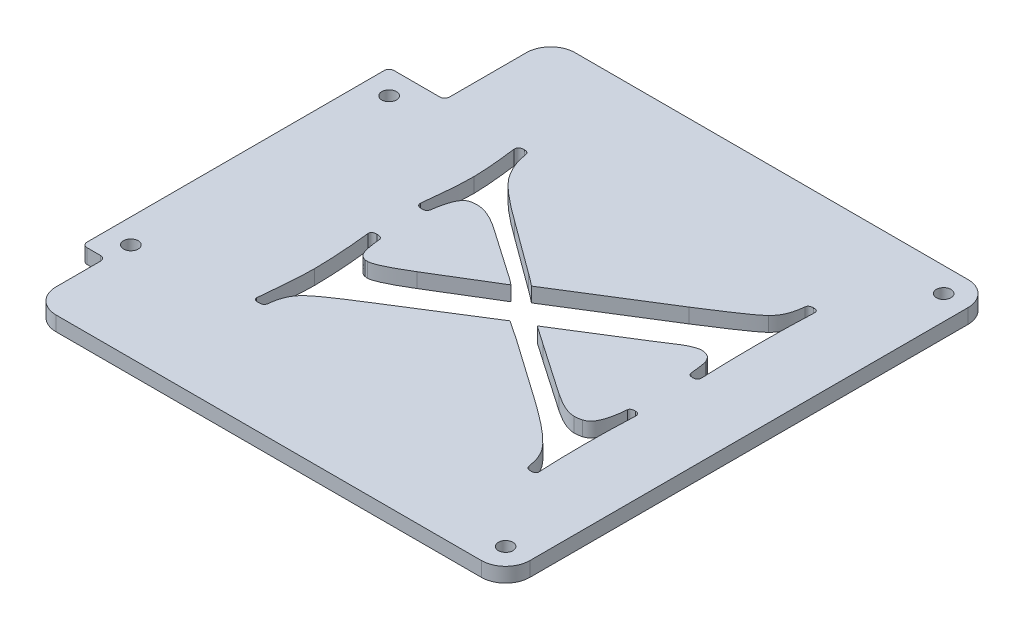
SolidWorks part; units mm, degrees
ref_plane "Front Plane" through (0, 0, 0) normal (0, 0, 1) x (1, 0, 0)
ref_plane "Top Plane" through (0, 0, 0) normal (0, 1, 0) x (1, 0, 0)
ref_plane "Right Plane" through (0, 0, 0) normal (1, 0, 0) x (0, 0, -1)
ref_plane "Plane1" through (0, 23, 0) normal (0, 1, 0) x (1, 0, 0)
sketch "Sketch1" plane through (0, 23, 0) normal (0, 1, 0) x (1, 0, 0)
  line L0 (98.3054, 50) -> (98.3054, 28.2195)
  line L1 (189.0458, 50) -> (98.3054, 50)
  line L2 (189.0458, 50) -> (189.0458, -50)
  line L3 (189.0458, -50) -> (97.6502, -50)
  line L5 (98.3054, 28.2195) -> (86.88, 28.2195)
  line L6 (86.88, 28.2195) -> (86.88, -34.8422)
  line L7 (86.88, -34.8422) -> (91.6598, -34.8422)
  line L8 (91.6598, -34.8422) -> (91.6598, -50)
  line L9 (91.6598, -50) -> (97.6502, -50)
  line L10 (94.8054, 33.2195) -> (98.3054, 33.2195) construction
  line L11 (184.0458, 45) -> (184.0458, 50) construction
  line L12 (93.3054, 31.7195) -> (93.3054, 28.2195) construction
  line L13 (99.4745, -34.8422) -> (86.1225, -34.8422) construction
  line L14 (88.1598, -39.8422) -> (91.6598, -39.8422) construction
  line L15 (86.6598, -38.3422) -> (86.6598, -34.8422) construction
  line L16 (189.0458, 0) -> (190, 0) construction
  line L17 (190, -60) -> (190, 60) construction
  line L18 (105.0183, -40) -> (185.0183, -40) construction
  line L19 (105.0183, -40) -> (105.0183, 40) construction
  line L20 (105.0183, 40) -> (185.0183, 40) construction
  line L21 (185.0183, -40) -> (185.0183, 40) construction
  line L22 (184.0458, 45) -> (189.0458, 45) construction
  line L23 (184.0458, -45) -> (189.0458, -45) construction
  line L24 (184.0458, -45) -> (184.0458, -50) construction
  line L25 (91.88, 23.2195) -> (91.88, 28.2195) construction
  line L26 (91.88, 23.2195) -> (86.88, 23.2195) construction
  line L27 (91.88, -29.8422) -> (91.88, -34.8422) construction
  line L28 (91.88, -29.8422) -> (86.88, -29.8422) construction
  circle A0 centre (86.6598, -39.8422) radius 1.5 construction
  circle A1 centre (93.3054, 33.2195) radius 1.5 construction
  circle A2 centre (184.0458, 45) radius 1.5 construction
  circle A3 centre (184.0458, 45) radius 1.5 construction
  circle A4 centre (184.0458, -45) radius 1.5 construction
  circle A6 centre (91.88, 23.2195) radius 1.5 construction
  circle A7 centre (91.88, -29.8422) radius 1.5 construction
  point P32 (185.0183, 0)
  dimension "D1" = 100
  dimension "D2" = 80
  dimension "D3" = 3.5
  dimension "D4" = 5
extrude "Boss-Extrude1" add sketch "Sketch1" along normal blind 3
fillet "Fillet3" radius 5 4 edges at (189.0458, 24.5, -50) (98.3054, 24.5, -50) (91.6598, 24.5, 50) (189.0458, 24.5, 50)
fillet "Fillet2" radius 1 4 edges at (86.88, 24.5, -28.2195) (98.3054, 24.5, -28.2195) (91.6598, 24.5, 34.8422) (86.88, 24.5, 34.8422)
sketch "Sketch2" plane through (0, 23, 0) normal (0, 1, 0) x (1, 0, 0)
  circle A0 centre (184.0458, -45) radius 1.5 construction
  circle A1 centre (184.0458, -45) radius 1.5
  circle A2 centre (91.88, -29.8422) radius 1.5 construction
  circle A3 centre (91.88, -29.8422) radius 1.5
  circle A4 centre (91.88, 23.2195) radius 1.5 construction
  circle A5 centre (91.88, 23.2195) radius 1.5
  circle A6 centre (184.0458, 45) radius 1.5 construction
  circle A7 centre (184.0458, 45) radius 1.5
extrude "Cut-Extrude1" cut sketch "Sketch2" along normal up to surface (3 mm away) up to face at (116.4727, 26, 1.6557)
sketch "Sketch4" plane through (0, 23, 0) normal (0, 1, 0) x (1, 0, 0)
  line L0 (176.5151, -28.0588) -> (176.5151, 28.0588) construction
  line L2 (150, 0) -> (182, 0) construction
  text T0 "X" font "@Yu Mincho Demibold" height 60
  point P3 (176.5151, 0)
  point P4 (176.323, 26.6982)
  point P5 (176.1974, 18.1721)
  point P6 (176.0881, 21.7791)
  point P7 (0, 0)
  point P8 (0, 0)
extrude "Cut-Extrude2" cut sketch "Sketch4" along normal up to surface (3 mm away) up to face at (184.0458, 26, 43.5)
